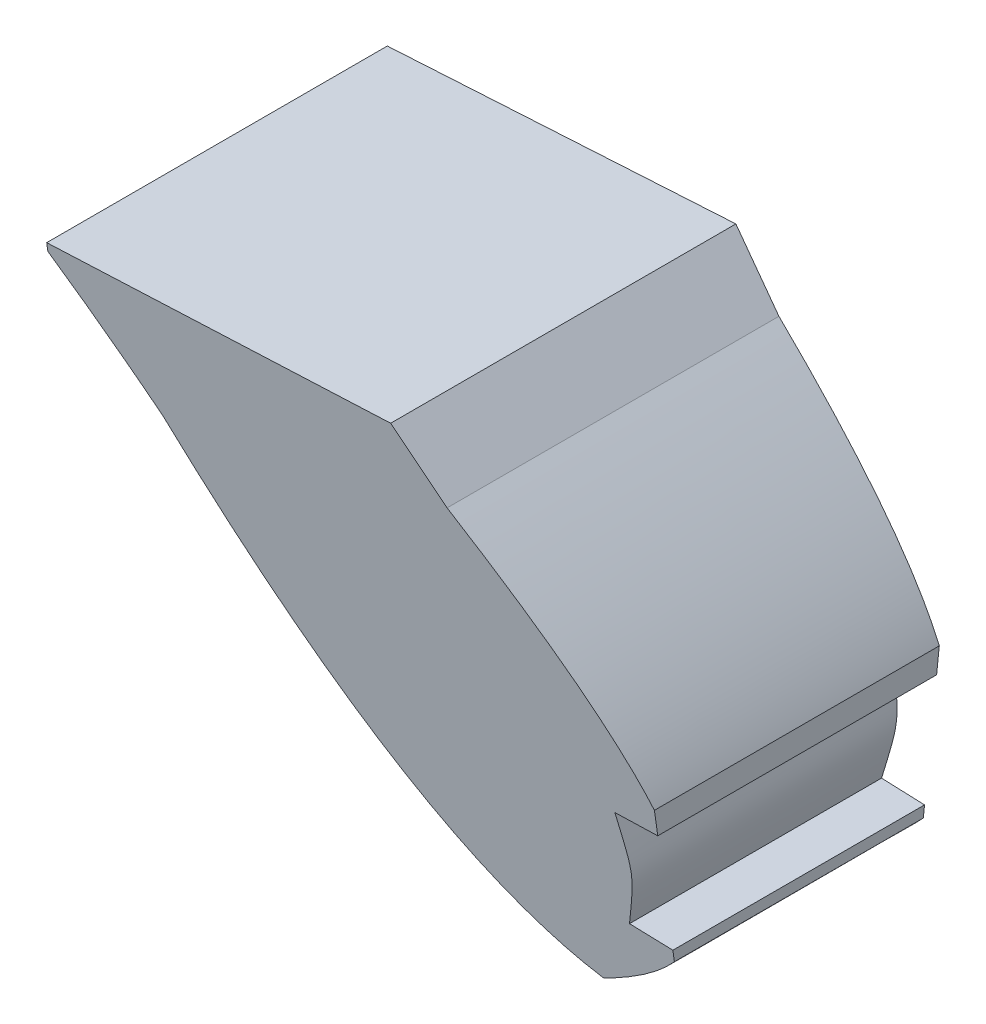
SolidWorks part; units mm, degrees
ref_plane "Alzado" through (0, 0, 0) normal (0, 0, 1) x (1, 0, 0)
ref_plane "Planta" through (0, 0, 0) normal (0, 1, 0) x (1, 0, 0)
ref_plane "Vista lateral" through (0, 0, 0) normal (1, 0, 0) x (0, 0, -1)
sketch "Croquis1" plane through (0, 0, 0) normal (0, 0, 1) x (1, 0, 0)
  line L0 (-8.9818, 12.6082) -> (-23.0359, 11.8716) construction
  line L1 (-8.9818, 12.6082) -> (-23.0359, 11.8716)
  line L2 (-8.9818, 12.6082) -> (-23.0359, 11.8716) construction
  line L4 (-8.9818, 12.6082) -> (-23.0359, 11.8716)
  line L6 (-1.3949, 1.9763) -> (0.3551, 2.2848) construction
  line L7 (-1.3949, 1.9763) -> (0.3551, 2.2848)
  line L8 (0.3551, 2.2848) -> (0.3551, 2.8423) construction
  line L9 (0.3551, 2.2848) -> (0.3551, 3.0015)
  line L10 (0.3551, -2.2848) -> (-1.3949, -2.2237) construction
  line L11 (0.3551, -2.2848) -> (-1.3949, -2.2237)
  line L12 (0.3551, 2.2848) -> (0.3551, -2.2848) construction
  line L13 (0.3551, -2.2848) -> (0.3551, -2.7233)
  line L14 (-8.9818, 12.6082) -> (-6.9949, 10.4774)
  line L15 (-23.0359, 11.5401) -> (-23.0359, 11.8716) construction
  line L16 (-23.0359, 11.5401) -> (-23.0359, 11.8716)
  arc A0 (-18.9452, 7.5409) -> (-23.0359, 11.5401) centre (-69.8841, -40.4718) ccw construction
  arc A1 (-18.9452, 7.5409) -> (-23.0359, 11.5401) centre (-69.8841, -40.4718) ccw
  spline S1 degree 2 poles (-828.7061, 3922.2202) (545.889, -3962.7836) (-262.0834, 3982.5902) knots 0.462185 0.462185 0.462185 0.537731 0.537731 0.537731 weights 1 1 1 only from (-18.9452, 7.5409) to (-2.8466, -5.0591) construction
  spline S2 degree 2 poles (-18.9452, 7.5409) (-10.215, -3.6976) (-2.8466, -5.0591) knots 0.497667 0.497667 0.497667 0.499554 0.499554 0.499554 weights 1 1 1
  spline S3 degree 2 poles (-3804.8689, 1232.5771) (3762.9122, -1369.6643) (-3716.5752, 1504.852) knots 0.462212 0.462212 0.462212 0.537836 0.537836 0.537836 weights 1 1 1 only from (0.3551, 3.0015) to (-6.9949, 10.4774) construction
  spline S4 degree 2 poles (0.3551, 3.0015) (-1.4487, 6.0584) (-6.9949, 10.4774) knots 0.500821 0.500821 0.500821 0.502013 0.502013 0.502013 weights 1 1 1
  spline S5 degree 2 poles (-1.3949, -2.2237) (-0.9075, -0.1237) (-1.3949, 1.9763) knots 0 0 0 1 1 1 weights 1 3.231801 1 construction
  spline S6 degree 2 poles (-1.3949, -2.2237) (-0.9075, -0.1237) (-1.3949, 1.9763) knots 0 0 0 1 1 1 weights 1 3.231801 1
  spline S7 degree 2 poles (-3997.263, 185.0077) (3984.2333, -348.7483) (-3965.0625, 511.2595) knots 0.462205 0.462205 0.462205 0.537778 0.537778 0.537778 weights 1 1 1 only from (-2.8466, -5.0591) to (0.3551, -2.7233) construction
  spline S8 degree 2 poles (-2.8466, -5.0591) (-0.7424, -3.9352) (0.3551, -2.7233) knots 0.498812 0.498812 0.498812 0.499413 0.499413 0.499413 weights 1 1 1
extrude "Saliente-Extruir1" add sketch "Croquis1" along normal mid plane 14 contours S2 S8 L13 L11 S6 L7 L9 S4 L14 L1 L16 A1
sketch "Croquis3" plane through (0, 0, 0) normal (0, 0, 1) x (1, 0, 0)
  line L0 (-6.742, 0) -> (0, 0) construction
  line L1 (-1.8181, 2) -> (-1.7771, 2.0103) construction
  line L3 (-1.8181, 2) -> (-0.1689, 2.4155) construction
  line L4 (-1.8181, 2) -> (0.3551, 3.0015)
  line L5 (0.3551, 3.0015) -> (0.3551, 0)
  line L6 (-1.9135, -2.1825) -> (0.3551, -2.2848)
  line L7 (0.3551, -2.2848) -> (0.3551, 0)
  parabola Q0 (-1.9135, -2.1825) -> (-1.8181, 2) focus (-3.3181, 0) apex (-1.3181, 0)
  dimension "D1" = 2
  dimension "D2" = 2
extrude "Cortar-Extruir1" [suppressed] cut sketch "Croquis3" against normal through all both and the other way through all
sketch "Croquis4" plane through (0, 0, 0) normal (0, 0, 1) x (1, 0, 0)
  line L0 (-1.3949, 1.9763) -> (0.3551, 2.2848) construction
  line L1 (-1.3949, 1.9763) -> (0.3551, 2.2848)
  line L2 (0.3551, 2.2848) -> (0.3551, 3.0015) construction
  line L3 (0.3551, 2.0374) -> (0.3551, 2.2848)
  line L4 (-1.3949, 1.9763) -> (0.3551, 2.0374)
  line L5 (0, 0) -> (-3.4665, 0) construction
  dimension "D1" = 2
extrude "Saliente-Extruir2" add sketch "Croquis4" along normal through all and the other way through all
sketch "Croquis7" plane through (0, 0, 0) normal (0, 0, 1) x (1, 0, 0)
  line L0 (0, 0) -> (-15.3945, 3.3171) construction
  line L1 (-17.3963, 18.9371) -> (-15.3945, 3.3171) construction
  line L2 (-15.3945, 3.3171) -> (-9.9316, -2.6296) construction
  line L3 (-15.3945, 3.3171) -> (-10.2385, 8.0535) construction
  line L4 (-17.3963, 18.9371) -> (-16.5429, 12.2783) construction
  line L5 (0, 0) -> (-1.3461, -2.2254) construction
  line L6 (-69.8841, 29.5282) -> (-81.9382, 42.5765) construction
  line L7 (-69.8841, 29.5282) -> (-20.9497, 29.5282) construction
  line L8 (-17.8101, 13.1658) -> (-25.5429, 13.1658)
  line L9 (-18.2059, 7.0951) -> (-21.9246, 11.9299) construction
  line L10 (0.3551, -2.5) -> (-2.4497, -2.0473)
  line L11 (-1.3461, -2.2254) -> (-2.0075, -3.6222) construction
  line L12 (-1.3461, -2.2254) -> (-1.4547, -2.8987) construction
  line L13 (-1.3461, -2.2254) -> (-1.2286, -1.4976) construction
  line L14 (0.3551, -2.2848) -> (0.3551, -2.7233) construction
  line L15 (0.3551, -2.2848) -> (-1.3949, -2.2237) construction
  line L16 (-2.0075, -3.6222) -> (-3.0629, -5.8512) construction
  line L17 (-2.6331, -4.9434) -> (-3.7044, -5.5324) construction
  line L18 (-2.6331, -4.9434) -> (-3.2248, -3.867) construction
  line L19 (-2.6331, -4.9434) -> (-2.2174, -6.1341) construction
  line L20 (-4.0838, -4.7637) -> (-1.6363, -5.0668) construction
  line L21 (-4.0838, -4.7637) -> (-0.036, -5.9454) construction
  line L22 (-4.0838, -4.7637) -> (-3.7621, -3.6616) construction
  line L23 (-4.0838, -4.7637) -> (-6.31, -3.7023) construction
  line L24 (-6.31, -3.7023) -> (-8.69, -2.5677) construction
  line L25 (-8.69, -2.5677) -> (-6.8421, -3.7725) construction
  line L26 (-8.69, -2.5677) -> (-7.9481, -1.4297) construction
  line L27 (-10.6884, -0.8477) -> (-8.69, -2.5677) construction
  line L28 (-10.6884, -0.8477) -> (-14.8546, 2.738) construction
  line L29 (-14.8546, 2.738) -> (-14.5337, 2.3989) construction
  line L30 (-14.8546, 2.738) -> (-14.6199, 2.9602) construction
  line L31 (-18.2059, 7.0951) -> (-14.8546, 2.738) construction
  line L32 (-8.9818, 12.6082) -> (-23.0359, 11.8716) construction
  line L33 (-8.9818, 12.6082) -> (-23.0359, 11.8716)
  line L34 (-21.9246, 11.9299) -> (-21.9826, 13.0367) construction
  line L35 (-21.9246, 11.9299) -> (-23.4156, 13.0367) construction
  arc A0 (-18.9452, 7.5409) -> (-23.0359, 11.5401) centre (-69.8841, -40.4718) ccw construction
  spline S0 degree 2 poles (-654.4568, 2937.5195) (409.3679, -2972.9237) (-163.476, 2987.5518) knots 0.467242 0.467242 0.467242 0.532662 0.532662 0.532662 weights 1 1 1 only from (-18.9452, 7.5409) to (-2.8466, -5.0591) construction
  spline S1 degree 2 poles (-18.6263, 7.1332) (-10.0803, -3.7225) (-2.8466, -5.0591) knots 0.497702 0.497702 0.497702 0.499554 0.499554 0.499554 weights 1 1 1 construction
  spline S3 degree 2 poles (-2999.4042, 119.7504) (2988.2948, -261.6206) (-2971.0465, 402.239) knots 0.467267 0.467267 0.467267 0.532713 0.532713 0.532713 weights 1 1 1 only from (-2.8466, -5.0591) to (0.3551, -2.7233) construction
  spline S4 degree 2 poles (-2.8466, -5.0591) (-2.7385, -5.0013) (-2.6331, -4.9434) knots 0.498812 0.498812 0.498812 0.498843 0.498843 0.498843 weights 1 1 1
  dimension "D1" = 2.5
  dimension "D2" = 22
  dimension "D3" = 16.17
  dimension "D4" = 54.138
  dimension "D5" = 34.566
  dimension "D6" = 50.413
sketch "Croquis6" plane through (0, 0, 0) normal (1, 0, 0) x (0, 0, -1)
  line L0 (7, 12.6082) -> (7, 10.4774) construction
  line L1 (7, 12.6082) -> (7, -5.0591)
  line L2 (-7, 12.6082) -> (-7, 10.4774) construction
  line L3 (-7, 12.6082) -> (-7, -5.0591)
  line L4 (-7, -5.0591) -> (7, -5.0591) construction
  line L5 (-7, -5.0591) -> (-4.5, -5.0591)
  line L6 (7, 12.6082) -> (5, -5.0591)
  line L7 (-7, 12.6082) -> (-4.5, -5.0591)
  line L8 (5, -5.0591) -> (7, -5.0591)
  dimension "D1" = 2.5
  dimension "D2" = 2
extrude "Cortar-Extruir2" cut sketch "Croquis6" against normal through all and the other way through all
